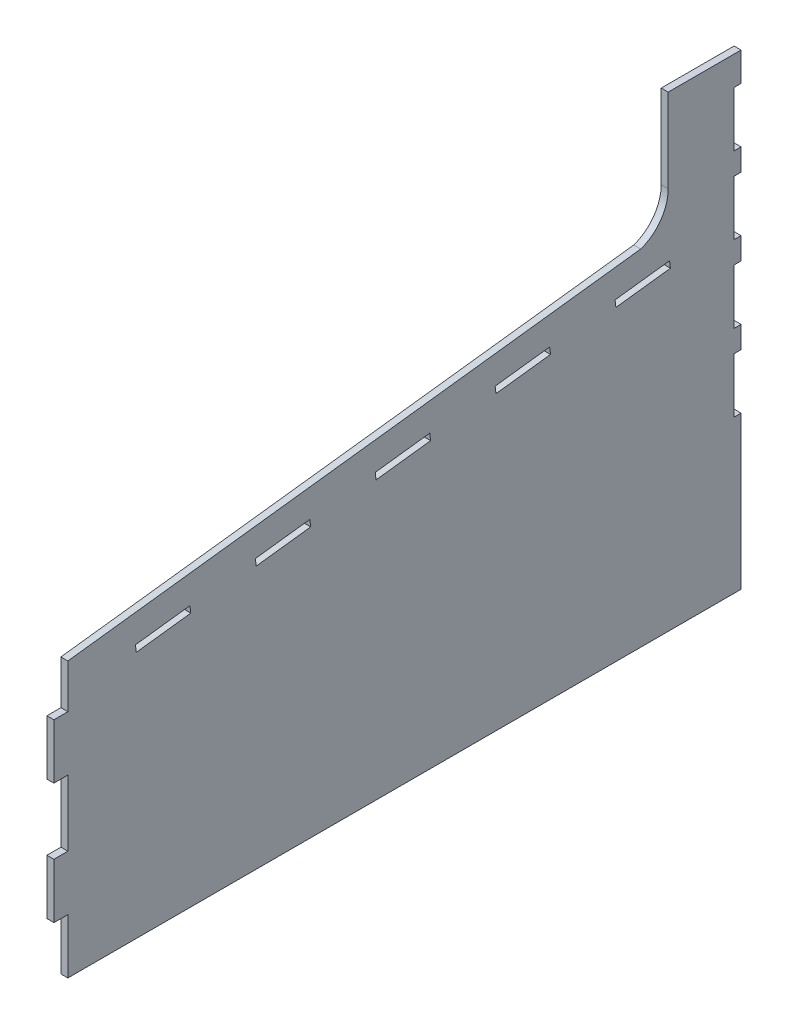
SolidWorks part; units mm, degrees
material "Beech"
ref_plane "Front Plane" through (0, 0, 0) normal (0, 0, 1) x (1, 0, 0)
ref_plane "Top Plane" through (0, 0, 0) normal (0, 1, 0) x (1, 0, 0)
ref_plane "Right Plane" through (0, 0, 0) normal (1, 0, 0) x (0, 0, -1)
sketch "Sketch1" plane through (0, 0, 0) normal (1, 0, 0) x (0, 0, -1)
  line L0 (0, 250) -> (521.6781, 314.054)
  line L1 (0, 0) -> (613, 0)
  line L2 (0, 0) -> (0, 50)
  line L4 (613, 0) -> (613, 138.97)
  line L6 (613, 258.9548) -> (613, 278.9396)
  line L7 (613, 425.2744) -> (546.65, 425.2744)
  line L8 (546.65, 349.0444) -> (546.65, 425.2744)
  line L9 (0, 250) -> (609, 250) construction
  line L10 (521.6781, 314.054) -> (613, 325.2669) construction
  line L11 (-12.7, 160) -> (-12.7, 210)
  line L12 (0, 50) -> (-12.7, 50)
  line L14 (0, 100) -> (-12.7, 100)
  line L15 (-12.7, 50) -> (-12.7, 100)
  line L16 (0, 160) -> (-12.7, 160)
  line L18 (0, 210) -> (-12.7, 210)
  line L19 (0, 210) -> (0, 250)
  line L21 (0, 100) -> (0, 160)
  line L23 (613, 398.9244) -> (606.65, 398.9244)
  line L25 (613, 348.9244) -> (606.65, 348.9244)
  line L26 (606.65, 398.9244) -> (606.65, 348.9244)
  line L28 (613, 328.9396) -> (606.65, 328.9396)
  line L29 (606.65, 328.9396) -> (606.65, 278.9396)
  line L30 (613, 278.9396) -> (606.65, 278.9396)
  line L32 (613, 258.9548) -> (606.65, 258.9548)
  line L33 (606.65, 258.9548) -> (606.65, 208.9548)
  line L34 (613, 208.9548) -> (606.65, 208.9548)
  line L36 (613, 188.97) -> (606.65, 188.97)
  line L37 (606.65, 188.97) -> (606.65, 138.97)
  line L38 (613, 138.97) -> (606.65, 138.97)
  line L39 (613, 188.97) -> (613, 208.9548)
  line L42 (613, 328.9396) -> (613, 348.9244)
  line L44 (613, 398.9244) -> (613, 425.2744)
  arc A0 (521.6781, 314.054) -> (546.65, 349.0444) centre (509.65, 349.0444) ccw
  dimension "D4" = 37
  dimension "D1" = 613
  dimension "D2" = 250
  dimension "D3" = 66.35
  dimension "D5" = 7
  dimension "D6" = 175.32
  dimension "D7" = 76.23
  dimension "D8" = 12.7
  dimension "D9" = 50
  dimension "D10" = 50
  dimension "D11" = 2
  dimension "D12" = 40
  dimension "D13" = 6.35
  dimension "D14" = 50
  dimension "D15" = 26.35
  dimension "D17" = 138.97
  dimension "D16" = 4
extrude "Boss-Extrude1" add sketch "Sketch1" along normal blind 6.35
sketch "Sketch2" plane through (6.35, 0, 0) normal (1, 0, 0) x (0, 0, -1)
  line L0 (521.6781, 314.054) -> (613, 325.2669) construction
  line L1 (613, 0) -> (613, 138.97) construction
  line L2 (521.6781, 314.054) -> (0, 250) construction
  line L3 (0, 224.4093) -> (613, 299.6762) construction
  line L4 (0, 50) -> (0, 0) construction
  line L5 (61.5379, 231.9651) -> (62.3117, 225.6625)
  line L6 (62.3117, 225.6625) -> (111.939, 231.7559)
  line L7 (111.939, 231.7559) -> (111.1652, 238.0586)
  line L8 (111.1652, 238.0586) -> (61.5379, 231.9651)
  line L9 (220.3452, 251.4642) -> (170.7179, 245.3708)
  line L10 (170.7179, 245.3708) -> (171.4918, 239.0681)
  line L11 (171.4918, 239.0681) -> (221.1191, 245.1616)
  line L12 (221.1191, 245.1616) -> (220.3452, 251.4642)
  line L13 (329.5253, 264.8699) -> (279.898, 258.7764)
  line L14 (279.898, 258.7764) -> (280.6719, 252.4737)
  line L15 (280.6719, 252.4737) -> (330.2992, 258.5672)
  line L16 (330.2992, 258.5672) -> (329.5253, 264.8699)
  line L17 (438.7054, 278.2755) -> (389.0781, 272.182)
  line L18 (389.0781, 272.182) -> (389.852, 265.8794)
  line L19 (389.852, 265.8794) -> (439.4793, 271.9728)
  line L20 (439.4793, 271.9728) -> (438.7054, 278.2755)
  line L21 (547.8855, 291.6811) -> (498.2582, 285.5877)
  line L22 (498.2582, 285.5877) -> (499.032, 279.285)
  line L23 (499.032, 279.285) -> (548.6593, 285.3785)
  line L24 (548.6593, 285.3785) -> (547.8855, 291.6811)
  dimension "D1" = 25.4
  dimension "D2" = 50
  dimension "D3" = 6.35
  dimension "D4" = 62
extrude "Cut-Extrude1" cut sketch "Sketch2" against normal blind 6.35
